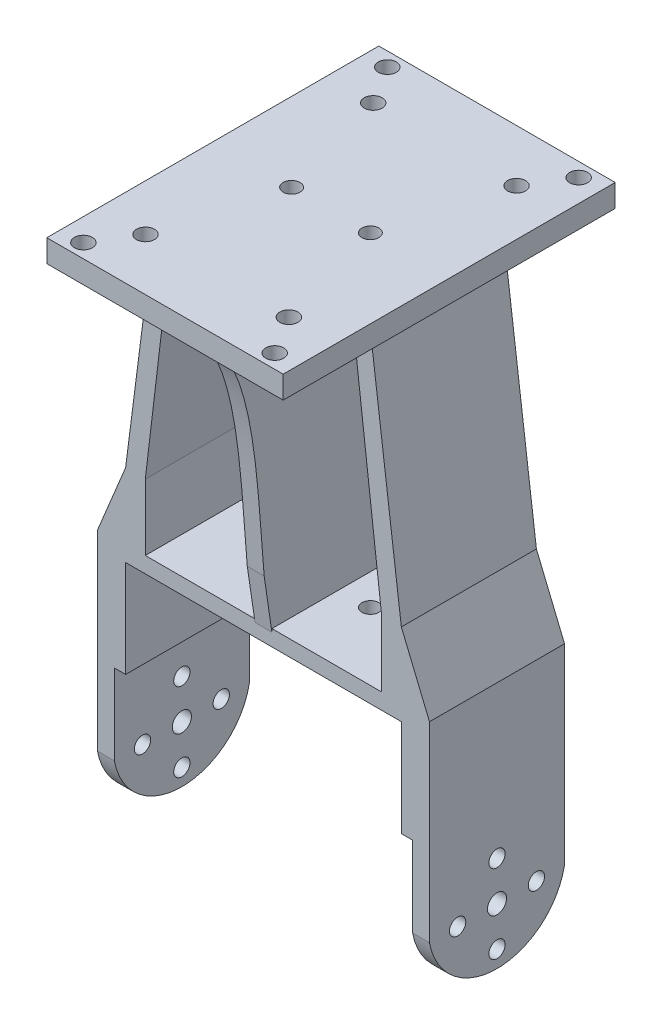
SolidWorks part; units mm, degrees
ref_plane "前视基准面" through (0, 0, 0) normal (0, 0, 1) x (1, 0, 0)
ref_plane "上视基准面" through (0, 0, 0) normal (0, 1, 0) x (1, 0, 0)
ref_plane "右视基准面" through (0, 0, 0) normal (1, 0, 0) x (0, 0, -1)
other "Configuration Table"
sketch "草图1" plane through (0, 0, 0) normal (0, 0, 1) x (1, 0, 0)
  line L5 (-29.5, 45) -> (29.5, 45)
  line L6 (-29.5, 45) -> (-29.5, -55)
  line L7 (-29.5, -55) -> (29.5, -55)
  line L8 (29.5, 45) -> (29.5, -55)
  point P0 (0, 0)
  dimension "D1" = 59
  dimension "D2" = 100
extrude "凸台-拉伸1" add sketch "草图1" along normal blind 24
sketch "草图2" plane through (0, 0, 24) normal (0, 0, 1) x (1, 0, 0)
  line L0 (-29.5, 45) -> (-29.5, -55) construction
  line L1 (29.5, -55) -> (-29.5, -55)
  line L2 (29.5, -55) -> (29.5, -20)
  line L3 (29.5, -20) -> (-29.5, -20)
  line L4 (-29.5, -55) -> (-29.5, -20)
sketch "草图3" plane through (-29.5, 0, 0) normal (-1, 0, 0) x (0, 0, 1)
  line L0 (12, -55) -> (12, -35) construction
  line L1 (24, -55) -> (0, -55) construction
  circle A0 centre (12, -45) radius 10 construction
  circle A1 centre (12, -45) radius 7 construction
  circle A2 centre (12, -38) radius 1.45
  circle A3 centre (12, -45) radius 1.7
  circle A4 centre (19, -45) radius 1.45
  circle A5 centre (12, -52) radius 1.45
  circle A6 centre (5, -45) radius 1.45
  point P19 (12, -45)
  dimension "D1" = 14
  dimension "D2" = 2.9
  dimension "D3" = 3.4
  dimension "D4" = 4
extrude "切除-拉伸1" cut sketch "草图3" against normal through all
sketch "草图4" plane through (0, 0, 24) normal (0, 0, 1) x (1, 0, 0)
  line L0 (0, -55.7156) -> (0, -30.7156) construction
  line L1 (-24.5, -30.7156) -> (-26.5, -30.7156)
  line L3 (-26.5, -30.7156) -> (-26.5, -55.7156)
  line L4 (-26.5, -55.7156) -> (26.5, -55.7156)
  line L5 (26.5, -30.7156) -> (26.5, -55.7156)
  line L6 (-26.5, -30.7156) -> (26.5, -55.7156) construction
  line L7 (-26.5, -55.7156) -> (26.5, -30.7156) construction
  line L8 (-24.5, -13.4831) -> (24.5, -13.4831)
  line L9 (-24.5, -13.4831) -> (-24.5, -30.7156)
  line L11 (24.5, -13.4831) -> (24.5, -30.7156)
  line L12 (-24.5, -13.4831) -> (24.5, -30.7156) construction
  line L13 (-24.5, -30.7156) -> (24.5, -13.4831) construction
  line L14 (24.5, -30.7156) -> (26.5, -30.7156)
  line L15 (29.5, -55) -> (29.5, 45) construction
  line L16 (-29.5, 45) -> (29.5, 45)
  line L17 (-29.5, 45) -> (-29.5, 5)
  line L19 (29.5, 45) -> (29.5, 5)
  line L20 (-29.5, 5) -> (-29.5, -5)
  line L23 (-18.8739, 45) -> (-24.5, 1.098)
  line L24 (-24.5, 1.098) -> (-29.5, -10.9915)
  line L25 (29.5, 5) -> (29.5, -5)
  line L31 (-1.5, 1.098) -> (-1.5, -10.6565)
  line L33 (0, -22.0994) -> (0, 45) construction
  line L34 (-1.5, 45) -> (1.5, 45)
  line L35 (-1.5, 45) -> (-1.5, 1.098)
  line L36 (1.5, 45) -> (1.5, 1.098)
  line L37 (-24.5, -13.4831) -> (-26.5, -13.4831)
  line L38 (-26.5, -13.4831) -> (-26.5, -30.7156)
  line L39 (24.5, -13.4831) -> (26.5, -13.4831)
  line L40 (26.5, -13.4831) -> (26.5, -30.7156)
  line L41 (-18.8739, 45) -> (-16, 45)
  line L42 (-16, 45) -> (-16, 1.098)
  line L43 (24.5, 1.098) -> (29.5, -10.9915)
  line L44 (-29.5, 45) -> (-29.5, -55) construction
  line L45 (18.8739, 45) -> (24.5, 1.098)
  line L46 (16, 45) -> (16, 1.098)
  line L47 (-21, 1.098) -> (21, 1.098)
  line L48 (-21, 1.098) -> (-21, -10.6565)
  line L49 (-21, -10.6565) -> (21, -10.6565)
  line L50 (21, 1.098) -> (21, -10.6565)
  line L51 (-21, 1.098) -> (21, -10.6565) construction
  line L52 (-21, -10.6565) -> (21, 1.098) construction
  line L53 (-16, 45) -> (-16, 43.004)
  line L54 (-16, 43.004) -> (16, 43.004)
  line L55 (-16, 43.004) -> (-21, 1.098)
  line L56 (16, 43.004) -> (21, 1.098)
  line L57 (1.5, 1.098) -> (1.5, -10.6565)
  point P3 (0, -43.2156)
  point P8 (0, -22.0994)
  point P21 (0, 25)
  point P29 (0, 45)
  point P42 (0, -4.7792)
  dimension "D4" = 1.5
  dimension "D1" = 25
  dimension "D2" = 53
  dimension "D3" = 49
extrude "切除-拉伸2" cut sketch "草图4" against normal through all
sketch "草图5" plane through (0, 45, 0) normal (0, 1, 0) x (1, 0, 0)
  line L0 (0, 0) -> (0, -24) construction
  line L8 (29.5, -24) -> (-29.5, -24) construction
  line L21 (-21, -12) -> (21, -12) construction
  line L24 (-17, 15) -> (-12.7375, 8.2301) construction
  line L25 (-21, 17.5) -> (21, 17.5)
  line L28 (-21, 17.5) -> (-21, -41.5)
  line L29 (-21, -41.5) -> (21, -41.5)
  line L30 (21, 17.5) -> (21, -41.5)
  line L31 (-21, 17.5) -> (21, -41.5) construction
  line L32 (-21, -41.5) -> (21, 17.5) construction
  line L37 (-17, 15) -> (17, -39) construction
  line L38 (-17, -39) -> (17, 15) construction
  circle A12 centre (-17, 15) radius 1.6
  circle A13 centre (-12.7375, 8.2301) radius 1.6
  circle A14 centre (12.7375, 8.2301) radius 1.6
  circle A15 centre (17, 15) radius 1.6
  circle A16 centre (17, -39) radius 1.6
  circle A17 centre (12.7375, -32.2301) radius 1.6
  circle A18 centre (-17, -39) radius 1.6
  circle A19 centre (-12.7375, -32.2301) radius 1.6
  point P4 (0, -12)
  point P10 (0, -12)
  point P15 (0, -12)
  dimension "D5" = 3.2
  dimension "D7" = 3.2
  dimension "D1" = 59
  dimension "D2" = 42
  dimension "D3" = 34
  dimension "D4" = 54
  dimension "D6" = 8
extrude "凸台-拉伸2" add sketch "草图5" along normal mid plane 4
ref_plane "基准面1" through (0, 0, 0) normal (1, 0, 0) x (0, 0, 1)
sketch "草图7" plane through (0, 0, 0) normal (1, 0, 0) x (0, 0, 1)
  line L2 (0, 5) -> (0, -43)
  line L5 (0, 5) -> (0, 11.2187)
  line L6 (12, 5) -> (12, 24.2114) construction
  line L7 (41.5, -43) -> (30.6629, -38.9901) construction
  line L8 (41.5, -43) -> (24, -43)
  line L9 (0, -43) -> (-17.5, -43)
  line L10 (24, 5) -> (24, -43)
  line L18 (24, 5) -> (24, 11.2187)
  line L19 (24, 11.2187) -> (25.3779, 1.8799)
  line L20 (30.6629, -38.9901) -> (26.9693, -28.6503) construction
  line L21 (26.9693, -28.6503) -> (26.4756, -10.792) construction
  line L22 (0, 11.2187) -> (-1.3779, 1.8799)
  line L23 (-17.5, -43) -> (-6.6629, -38.9901) construction
  line L24 (26.4756, -10.792) -> (25.3779, 1.8799) construction
  line L25 (-6.6629, -38.9901) -> (-2.9693, -28.6503) construction
  line L26 (-2.9693, -28.6503) -> (-2.4756, -10.792) construction
  line L27 (-2.4756, -10.792) -> (-1.3779, 1.8799) construction
  spline S0 degree 4 poles (-17.5, -43) (-6.6629, -38.9901) (-2.9693, -28.6503) (-2.4756, -10.792) (-1.3779, 1.8799) knots 0 0 0 0 0 1 1 1 1 1
  spline S1 degree 4 poles (41.5, -43) (30.6629, -38.9901) (26.9693, -28.6503) (26.4756, -10.792) (25.3779, 1.8799) knots 0 0 0 0 0 1 1 1 1 1
extrude "凸台-拉伸3" add sketch "草图7" along normal mid plane 3
sketch "草图8" plane through (29.5, 0, 0) normal (1, 0, 0) x (0, 0, -1)
  line L0 (-12, -45) -> (-24, -45)
  line L1 (-24, -55) -> (-24, -20) construction
  line L2 (-12, -45) -> (-12, -55) construction
  arc A2 (0, -45) -> (-24, -45) centre (-12, -42.8) cw
  line M10 (0, -55) -> (0, -10.9915)
  line M12 (-24, -10.9915) -> (-24, -55)
  line M13 (-24, -55) -> (0, -55)
extrude "切除-拉伸3" cut sketch "草图8" against normal through all and the other way through all contours A2 M13 M12 | A2 M10 M13
sketch "草图9" plane through (0, 47, 0) normal (0, 1, 0) x (1, 0, 0)
  circle A0 centre (0, -12) radius 7 construction
  circle A1 centre (0, -5) radius 1.5
  circle A2 centre (0, -12) radius 1.5
  circle A3 centre (7, -12) radius 1.5
  circle A4 centre (0, -19) radius 1.5
  circle A5 centre (-7, -12) radius 1.5
  point P15 (0, -12)
  dimension "D1" = 14
  dimension "D2" = 3
  dimension "D3" = 3
  dimension "D4" = 4
extrude "切除-拉伸4" cut sketch "草图9" against normal through all contours A5 | A3
